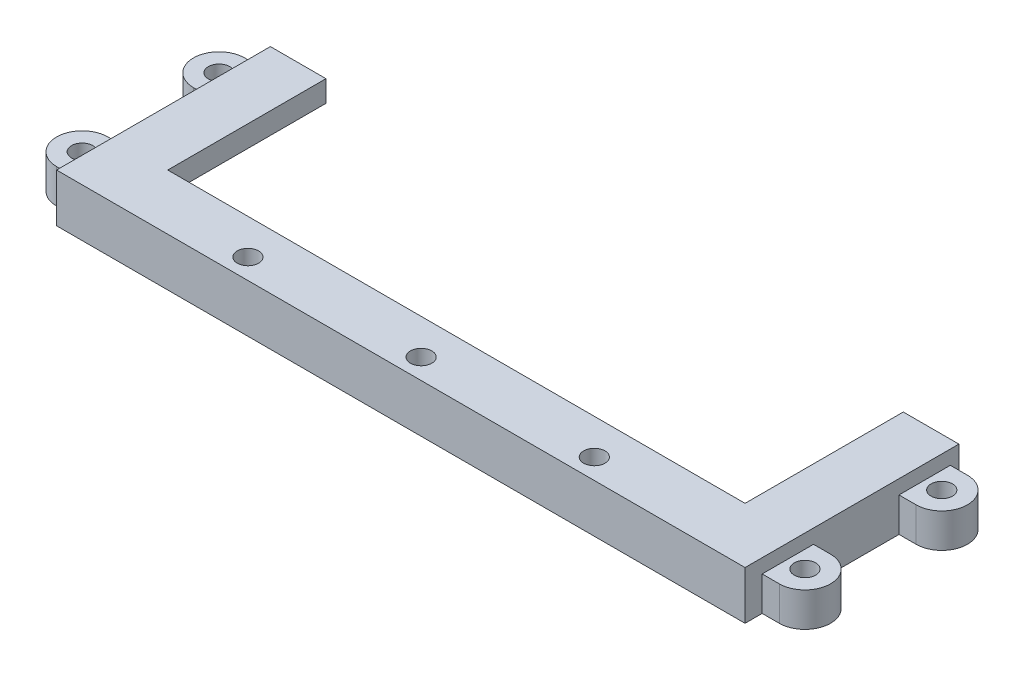
SolidWorks part; units mm, degrees
ref_plane "Alzado" through (0, 0, 0) normal (0, 0, 1) x (1, 0, 0)
ref_plane "Planta" through (0, 0, 0) normal (0, 1, 0) x (1, 0, 0)
ref_plane "Vista lateral" through (0, 0, 0) normal (1, 0, 0) x (0, 0, -1)
sketch "Croquis1" plane through (0, 0, 0) normal (0, 0, 1) x (1, 0, 0)
  line L0 (0, 0) -> (0, 11.3)
  line L1 (0, 11.3) -> (13, 11.3)
  line L2 (13, 11.3) -> (13, 6.3)
  line L3 (13, 6.3) -> (5, 6.3)
  line L4 (5, 6.3) -> (5, 0)
  line L5 (5, 0) -> (0, 0)
  dimension "D1" = 6.3
  dimension "D2" = 5
  dimension "D3" = 8
  dimension "D4" = 5
sketch "Croquis3" plane through (0, 0, 0) normal (0, 1, 0) x (1, 0, 0)
  line L0 (0, 0) -> (0, -37)
  dimension "D1" = 37
sweep "Barrer1" add profiles "Croquis1" path "Croquis3"
ref_plane "Plano1" through (80.5, 0, 0) normal (-1, 0, 0) x (0, 0, 1)
sketch "Croquis4" plane through (0, 0, 0) normal (-1, 0, 0) x (0, 0, 1)
  line L0 (0, 0) -> (37, 0) construction
  line L1 (37, 11.3) -> (50, 11.3)
  line L2 (37, 11.3) -> (37, 0)
  line L3 (37, 0) -> (50, 0)
  line L4 (50, 11.3) -> (50, 0)
  dimension "D1" = 13
extrude "Saliente-Extruir1" add sketch "Croquis4" against normal blind 161
mirror "Simetría5" about plane through (80.5, 0, 0) normal (-1, 0, 0) of "Barrer1"
sketch "Croquis5" plane through (0, 0, 0) normal (0, -1, 0) x (1, 0, 0)
  line L1 (5, 37) -> (156, 37)
  line L2 (5, 37) -> (5, 40.5)
  line L3 (5, 40.5) -> (156, 40.5)
  line L4 (156, 37) -> (156, 40.5)
  dimension "D1" = 3.5
  dimension "D2" = 151
extrude "Cortar-Extruir1" cut sketch "Croquis5" against normal blind 6.3
sketch "Croquis6" plane through (0, 0, 50) normal (0, 0, 1) x (1, 0, 0)
  line L0 (161, 11.3) -> (0, 11.3) construction
  line L1 (16, 11.3) -> (26, 11.3)
  line L2 (16, 11.3) -> (16, 14)
  line L4 (26, 11.3) -> (26, 14)
  line L5 (0, 0) -> (0, 11.3) construction
  arc A0 (26, 14) -> (16, 14) centre (21, 14) ccw
  dimension "D1" = 2.7
  dimension "D2" = 10
  dimension "D3" = 21
extrude "Saliente-Extruir2" [suppressed] add sketch "Croquis6" against normal blind 10
sketch "Croquis7" [suppressed] plane through (0, 0, 50) normal (0, 0, 1) x (1, 0, 0)
  circle A0 centre (21, 14) radius 3
  dimension "D1" = 6
extrude "Cortar-Extruir2" [suppressed] cut sketch "Croquis7" against normal through all
mirror "Simetría6" [suppressed] about plane through (80.5, 0, 0) normal (-1, 0, 0)
sketch "Croquis8" plane through (0, 0, 0) normal (0, -1, 0) x (1, 0, 0)
  line L0 (161, 0) -> (161, 50) construction
  line L1 (161, 46) -> (165, 46)
  line L2 (161, 46) -> (161, 34)
  line L3 (161, 34) -> (165, 34)
  line L5 (161, 50) -> (0, 50) construction
  arc A0 (165, 34) -> (165, 46) centre (165, 40) ccw
  dimension "D1" = 4
  dimension "D2" = 12
  dimension "D3" = 10
extrude "Saliente-Extruir3" add sketch "Croquis8" against normal blind 8
sketch "Croquis9" plane through (0, 0, 0) normal (0, -1, 0) x (1, 0, 0)
  circle A0 centre (165, 40) radius 2.5
  dimension "D1" = 5
extrude "Cortar-Extruir3" cut sketch "Croquis9" against normal through all
ref_plane "Plano2" through (0, 0, 24) normal (0, 0, -1) x (-1, 0, 0)
mirror "Simetría7" about plane through (0, 0, 24) normal (0, 0, -1) of "Saliente-Extruir3", "Cortar-Extruir3"
mirror "Simetría8" about plane through (80.5, 0, 0) normal (-1, 0, 0) of "Simetría7", "Saliente-Extruir3", "Cortar-Extruir3"
sketch "Croquis10" plane through (0, 11.3, 0) normal (0, 1, 0) x (1, 0, 0)
  line L0 (161, -50) -> (161, 0) construction
  line L1 (161, -50) -> (0, -50) construction
  circle A0 centre (121, -45.25) radius 2.5
  dimension "D3" = 5
  dimension "D1" = 40
  dimension "D2" = 4.75
extrude "Cortar-Extruir4" cut sketch "Croquis10" against normal through all
pattern_linear "MatrizL1" count 3 spacing 40.5 along (-1, 0, 0) of "Cortar-Extruir4"
